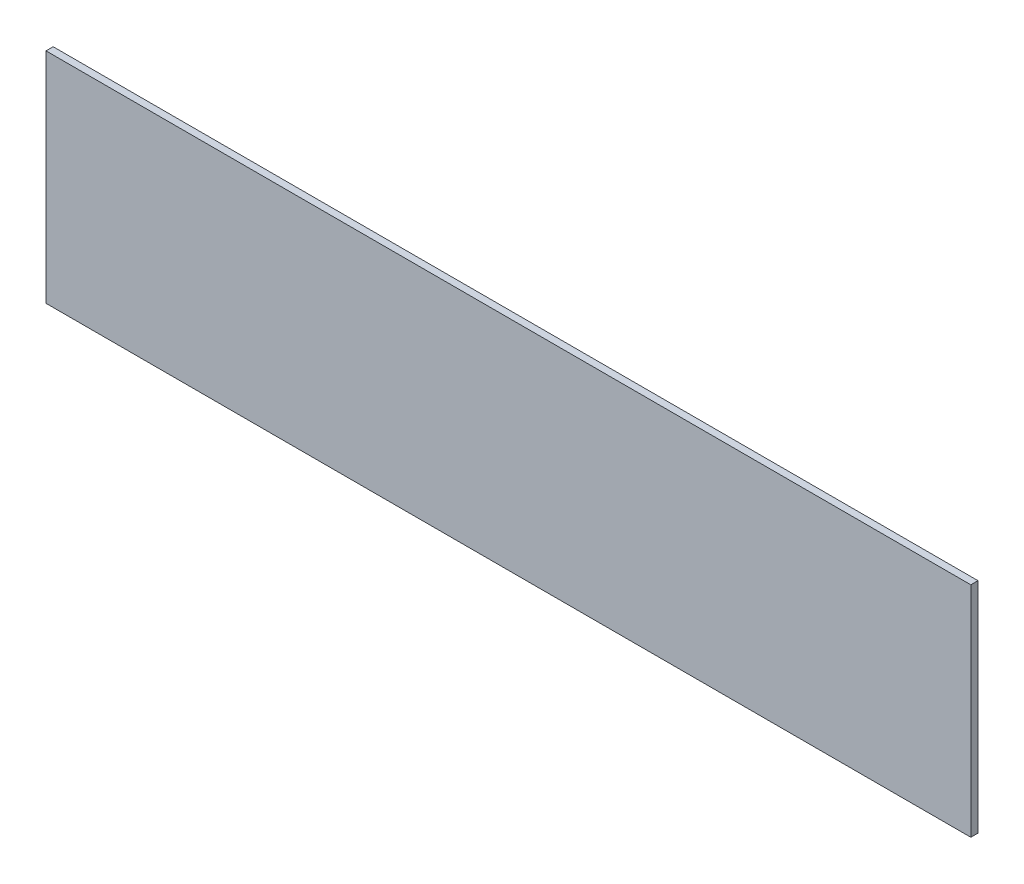
SolidWorks part; units mm, degrees
ref_plane "Front Plane" through (0, 0, 0) normal (0, 0, 1) x (1, 0, 0)
ref_plane "Top Plane" through (0, 0, 0) normal (0, 1, 0) x (1, 0, 0)
ref_plane "Right Plane" through (0, 0, 0) normal (1, 0, 0) x (0, 0, -1)
sketch "Sketch1" plane through (0, 0, 0) normal (0, 0, 1) x (1, 0, 0)
  line L1 (-258, -61) -> (185.4858, -61)
  line L2 (-258, -61) -> (-258, 61)
  line L3 (-258, 61) -> (258, 61)
  line L4 (258, -61) -> (258, 61)
  line L5 (-258, -61) -> (258, 61) construction
  line L6 (-258, 61) -> (258, -61) construction
  line L9 (185.4858, -61) -> (258, -61)
  point P0 (0, 0)
  point P8 (0, 0)
  point P22 (0, 0)
  dimension "D1" = 516
  dimension "D2" = 122
extrude "Boss-Extrude1" add sketch "Sketch1" along normal blind 4
